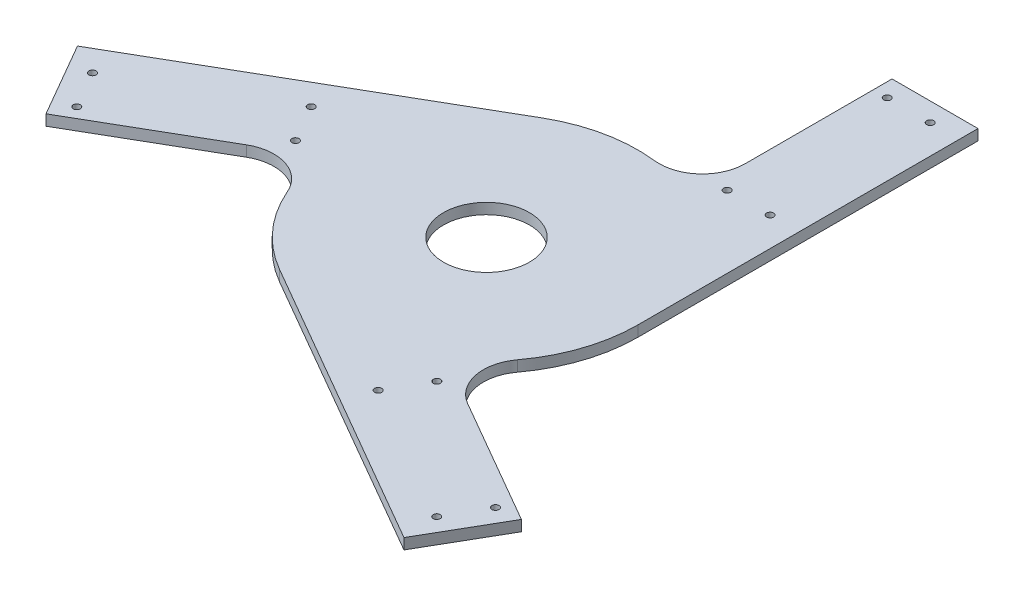
SolidWorks part; units mm, degrees
ref_plane "정면" through (0, 0, 0) normal (0, 0, 1) x (1, 0, 0)
ref_plane "윗면" through (0, 0, 0) normal (0, 1, 0) x (1, 0, 0)
ref_plane "우측면" through (0, 0, 0) normal (1, 0, 0) x (0, 0, -1)
sketch "스케치2" plane through (0, 0, 0) normal (0, 1, 0) x (1, 0, 0)
  line L0 (30.51, 63.5673) -> (30.51, 158.25)
  line L1 (30.51, 158.25) -> (70.51, 158.25)
  line L2 (70.51, 158.25) -> (70.51, 0)
  line L3 (-35.255, -61.0635) -> (101.7935, -140.1885)
  line L4 (101.7935, -140.1885) -> (121.7935, -105.5474)
  line L5 (121.7935, -105.5474) -> (39.7959, -58.2061)
  line L6 (-35.255, 61.0635) -> (-172.3035, -18.0615)
  line L7 (-172.3035, -18.0615) -> (-152.3035, -52.7026)
  line L8 (-152.3035, -52.7026) -> (-70.3059, -5.3612)
  circle A0 centre (0, 0) radius 70.51
  arc A1 (56.5566, -42.1072) -> (62.5987, -71.3713) centre (72.5987, -54.0508) ccw
  arc A2 (-93.1087, -18.5264) -> (-64.7442, -27.9258) centre (-83.1087, -35.8469) cw
  arc A3 (8.1876, 70.033) -> (30.51, 89.8977) centre (10.51, 89.8977) ccw
  dimension "D8" = 40
  dimension "D13" = 141.02
  dimension "D15" = 20
  dimension "D16" = 20
  dimension "20" = 20
  dimension "D2" = 40
  dimension "D3" = 30.51
  dimension "D4" = 158.25
  dimension "D5" = 120
  dimension "D6" = 158.25
  dimension "D7" = 40
  dimension "D9" = 120
  dimension "D10" = 158.25
  dimension "D11" = 30.51
  dimension "D12" = 30.51
extrude "보스-돌출1" add sketch "스케치2" along normal blind 5 contours A0 L6 L7 L8 | L8 A2 A0 | A0 | A0 L3 L4 L5 | A1 A0 L5 | A0 L2 L1 L0 | A3 A0 L0
sketch "스케치3" plane through (0, 5, 0) normal (0, 1, 0) x (1, 0, 0)
  circle A0 centre (0, 0) radius 20
  dimension "D1" = 40
extrude "컷-돌출1" cut sketch "스케치3" against normal through all
hole_wizard "M4 나사 구멍1" positions "스케치4" profile "스케치5" tap size "M4" standard "ISO" end condition through all
sketch "스케치4" plane through (0, 5, 0) normal (0, 1, 0) x (1, 0, 0)
  line L1 (37.01, 75) -> (57.01, 75) construction
  line L2 (37.01, 75) -> (37.01, 149.5) construction
  line L3 (37.01, 149.5) -> (57.01, 149.5) construction
  line L4 (57.01, 75) -> (57.01, 149.5) construction
  line L5 (37.01, 75) -> (57.01, 149.5) construction
  line L6 (37.01, 149.5) -> (57.01, 75) construction
  line L9 (30.51, 89.8977) -> (30.51, 158.25) construction
  line L11 (-4.5185, 100) -> (96.2514, 100) construction
  line L13 (30.51, 158.25) -> (70.51, 158.25) construction
  point P2 (57.01, 149.5)
  point P19 (37.01, 75)
  point P20 (37.01, 149.5)
  point P21 (57.01, 75)
  point P48 (100.9658, -124.1221)
  point P49 (46.4469, -69.5516)
  point P50 (110.9658, -106.8016)
  point P51 (36.4469, -86.8721)
  point P52 (-157.9758, -25.3779)
  point P53 (-83.4569, -5.4484)
  point P54 (-147.9758, -42.6984)
  point P55 (-93.4569, 11.8721)
  dimension "D1" = 20
  dimension "D2" = 6.5
  dimension "D3" = 49.5
  dimension "D4" = 74.5
  dimension "D6" = 100
  dimension "D7" = 8.75
  dimension "D5" = 3
sketch "스케치5" plane through (57.01, 5, -149.5) normal (1, 0, 0) x (0, 0, 1)
  line L0 (0, 0) -> (0, 5)
  line L1 (0, 5) -> (1.65, 5)
  line L2 (1.65, 5) -> (1.65, 0)
  line L5 (1.65, 0) -> (0, 0)
  line L11 (0, -6.35) -> (0, 107.95) construction
  dimension "관통 탭 드릴 지름" = 3.3
  dimension "관통 탭 드릴 깊이" = 5
cosmetic thread "구멍 나사산1" parameters "D2"=4
cosmetic thread "구멍 나사산2" parameters "D2"=4
cosmetic thread "구멍 나사산3" parameters "D2"=4
cosmetic thread "구멍 나사산4" parameters "D2"=4
cosmetic thread "구멍 나사산5" parameters "D2"=4
cosmetic thread "구멍 나사산6" parameters "D2"=4
cosmetic thread "구멍 나사산7" parameters "D2"=4
cosmetic thread "구멍 나사산8" parameters "D2"=4
cosmetic thread "구멍 나사산9" parameters "D2"=4
cosmetic thread "구멍 나사산10" parameters "D2"=4
cosmetic thread "구멍 나사산11" parameters "D2"=4
cosmetic thread "구멍 나사산12" parameters "D2"=4
